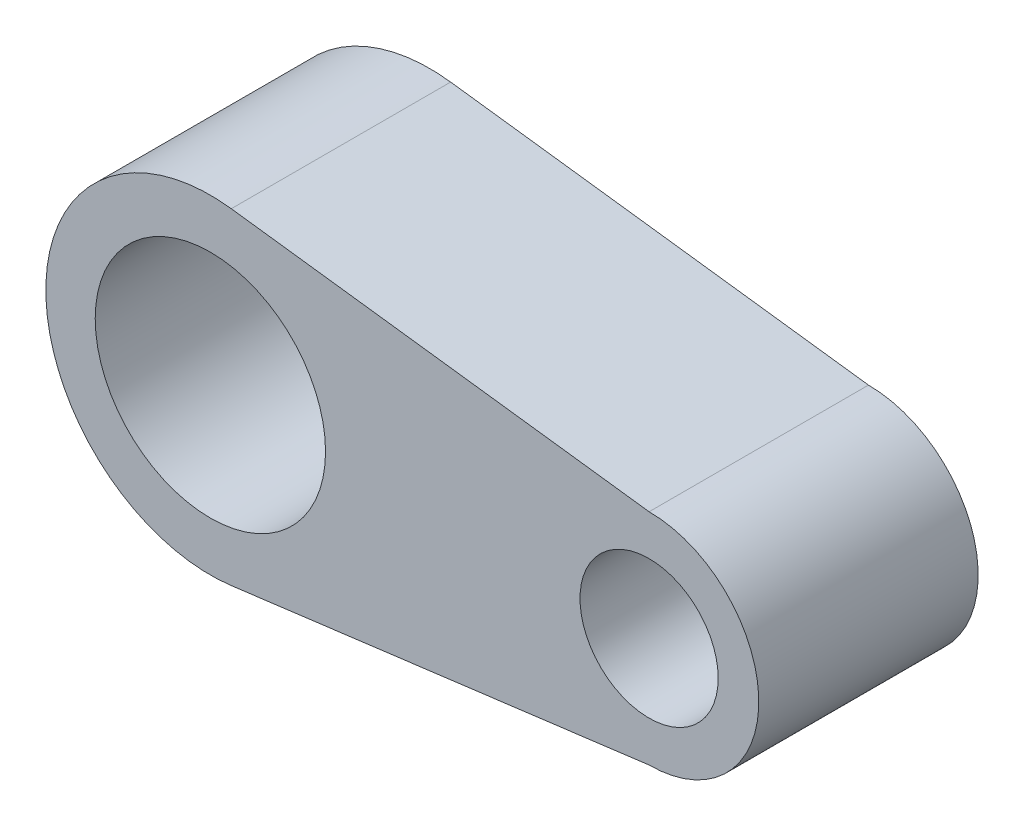
SolidWorks part; units mm, degrees
ref_plane "Front Plane" through (0, 0, 0) normal (0, 0, 1) x (1, 0, 0)
ref_plane "Top Plane" through (0, 0, 0) normal (0, 1, 0) x (1, 0, 0)
ref_plane "Right Plane" through (0, 0, 0) normal (1, 0, 0) x (0, 0, -1)
sketch "Sketch1" plane through (0, 0, 0) normal (0, 0, 1) x (1, 0, 0)
  line L0 (0, 0) -> (20, 0) construction
  line L1 (20, 5) -> (0.9527, 7.4392)
  line L2 (20, -5) -> (0.9527, -7.4392)
  circle A0 centre (0, 0) radius 5.25
  circle A1 centre (0, 0) radius 7.5
  circle A2 centre (20, 0) radius 5
  circle A3 centre (20, 0) radius 3.15
  dimension "D1" = 10.5
  dimension "D2" = 15
  dimension "D4" = 10
  dimension "D5" = 6.3
  dimension "D3" = 20
extrude "Boss-Extrude1" add sketch "Sketch1" along normal blind 10
